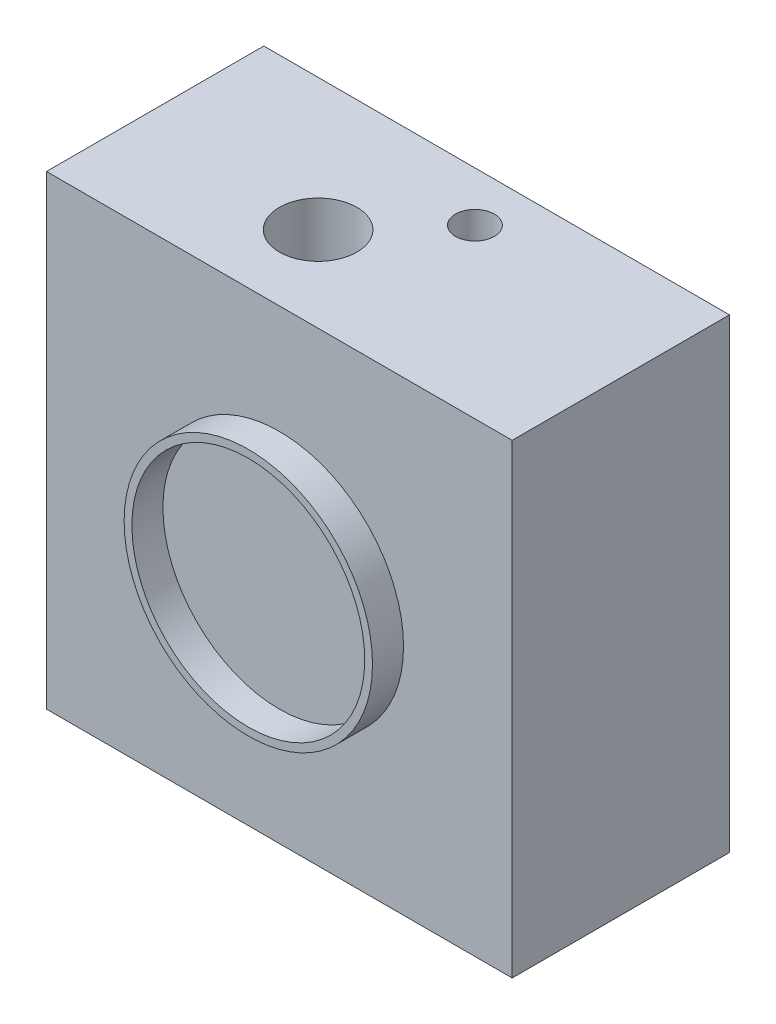
SolidWorks part; units mm, degrees
material "6061 合金"
ref_plane "前视基准面" through (0, 0, 0) normal (0, 0, 1) x (1, 0, 0)
ref_plane "上视基准面" through (0, 0, 0) normal (0, 1, 0) x (1, 0, 0)
ref_plane "右视基准面" through (0, 0, 0) normal (1, 0, 0) x (0, 0, -1)
sketch "草图1" plane through (0, 0, 0) normal (0, 0, 1) x (1, 0, 0)
  line L1 (-15, 15) -> (15, 15)
  line L2 (-15, 15) -> (-15, -15)
  line L3 (-15, -15) -> (15, -15)
  line L4 (15, 15) -> (15, -15)
  line L5 (-15, 15) -> (15, -15) construction
  line L6 (-15, -15) -> (15, 15) construction
  point P0 (0, 0)
  dimension "D1" = 30
  dimension "D2" = 30
extrude "凸台-拉伸1" add sketch "草图1" along normal blind 14
sketch "草图2" plane through (0, 0, 14) normal (0, 0, 1) x (1, 0, 0)
  circle A0 centre (0, 0) radius 7.5
  circle A1 centre (0, 0) radius 8
  dimension "D1" = 15
  dimension "D2" = 16
extrude "凸台-拉伸2" add sketch "草图2" along normal blind 2
sketch "草图3" plane through (0, 15, 0) normal (0, 1, 0) x (1, 0, 0)
  line L0 (0, -14) -> (0, 0) construction
  line L3 (15, -14) -> (-15, -14) construction
  line L4 (-8, -14) -> (8, -14) construction
  circle A1 centre (-3, -8.5) radius 2.5
  dimension "D1" = 5
  dimension "D2" = 5.5
  dimension "D3" = 3
extrude "切除-拉伸1" cut sketch "草图3" against normal blind 15
sketch "草图5" plane through (0, 15, 0) normal (0, 1, 0) x (1, 0, 0)
  line L0 (0, -14) -> (0, 0) construction
  line L1 (-8, -14) -> (8, -14) construction
  line L2 (15, -14) -> (-15, -14) construction
  point P5 (1.8, -3.2)
  dimension "D1" = 1.8
  dimension "D2" = 10.8
hole_wizard "M3 螺纹孔1" positions "3D草图2" profile "草图7" tap size "M3" standard "IS"
sketch3d "3D草图2"
  point P0 (1.8, 15, 3.2)
sketch "草图7" plane through (1.8, 15, 3.2) normal (1, 0, 0) x (0, 0, 1)
  line L0 (0, 0) -> (0, 8.2511)
  line L1 (0, 8.2511) -> (1.25, 7.5)
  line L2 (1.25, 7.5) -> (1.25, 0)
  line L5 (1.25, 0) -> (0, 0)
  line L10 (0, 8.2511) -> (-1.25, 7.5) construction
  line L11 (0, -6.35) -> (0, 107.95) construction
  dimension "螺纹孔钻头直径" = 2.5
  dimension "螺纹孔钻头深度" = 7.5
  dimension "导头角度" = 118
cosmetic thread "孔螺蚊线1" parameters "D1"=6, "D2"=3
sketch "草图8" plane through (0, 0, 0) normal (0, 0, -1) x (-1, 0, 0)
  line L1 (-9, 9) -> (9, 9) construction
  line L2 (-9, 9) -> (-9, -9) construction
  line L3 (-9, -9) -> (9, -9) construction
  line L4 (9, 9) -> (9, -9) construction
  line L5 (-9, 9) -> (9, -9) construction
  line L6 (-9, -9) -> (9, 9) construction
  point P0 (0, 0)
  dimension "D1" = 18
hole_wizard "孔1" positions "3D草图3" profile "草图9" legacy
sketch3d "3D草图3"
  line L0 (9, 9, 0) -> (9, -9, 0) construction
  point P0 (9, 8.9169, 0)
  point P4 (-9, 9, 0)
  point P7 (-9, -9, 0)
  point P10 (9, -9, 0)
sketch "草图9" plane through (9, 8.9169, 0) normal (1, 0, 0) x (0, 1, 0)
  line L0 (0, 0) -> (0, 9)
  line L1 (0, 9) -> (1.5, 9)
  line L2 (1.5, 9) -> (1.5, 5)
  line L3 (1.5, 5) -> (3, 5)
  line L4 (3, 5) -> (3, 0)
  line L5 (3, 0) -> (0, 0)
  line L6 (0, 110) -> (0, -10) construction
  dimension "直径" = 3
  dimension "深度" = 9
  dimension "柱坑直径" = 6
  dimension "柱坑深度" = 5
